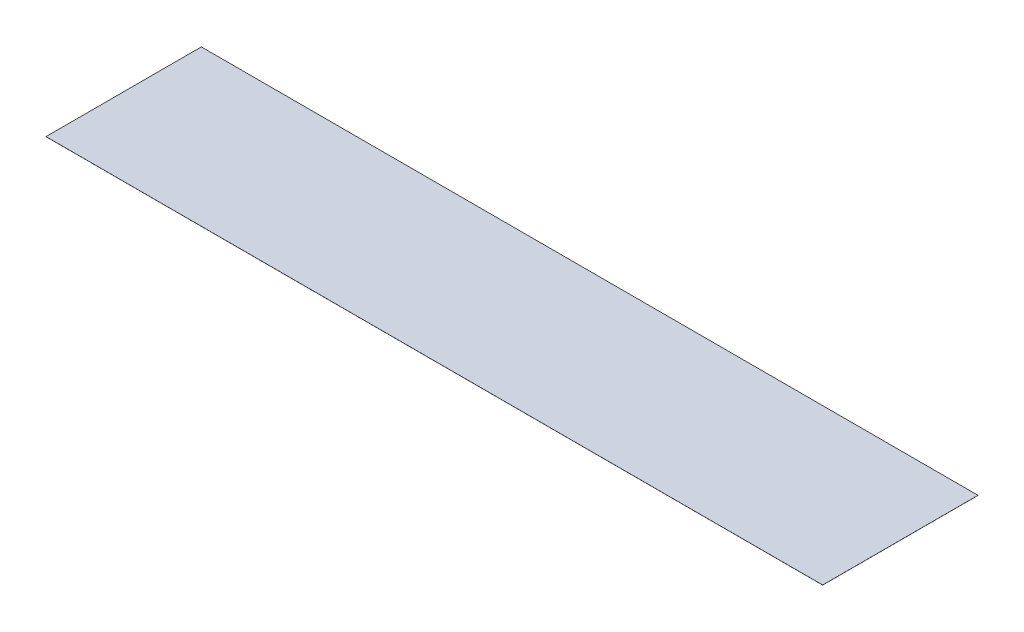
SolidWorks part; units mm, degrees
ref_plane "前视基准面" through (0, 0, 0) normal (0, 0, 1) x (1, 0, 0)
ref_plane "上视基准面" through (0, 0, 0) normal (0, 1, 0) x (1, 0, 0)
ref_plane "右视基准面" through (0, 0, 0) normal (1, 0, 0) x (0, 0, -1)
other "Configuration Table"
sketch "草图1" plane through (0, 0, 0) normal (0, 1, 0) x (1, 0, 0)
  line L1 (-750, -150) -> (750, -150)
  line L2 (-750, -150) -> (-750, 150)
  line L3 (-750, 150) -> (750, 150)
  line L4 (750, -150) -> (750, 150)
  line L5 (-750, -150) -> (750, 150) construction
  line L6 (-750, 150) -> (750, -150) construction
  point P0 (0, 0)
  dimension "D1" = 1500
  dimension "D2" = 300
extrude "凸台-拉伸1" add sketch "草图1" along normal blind 0.2
